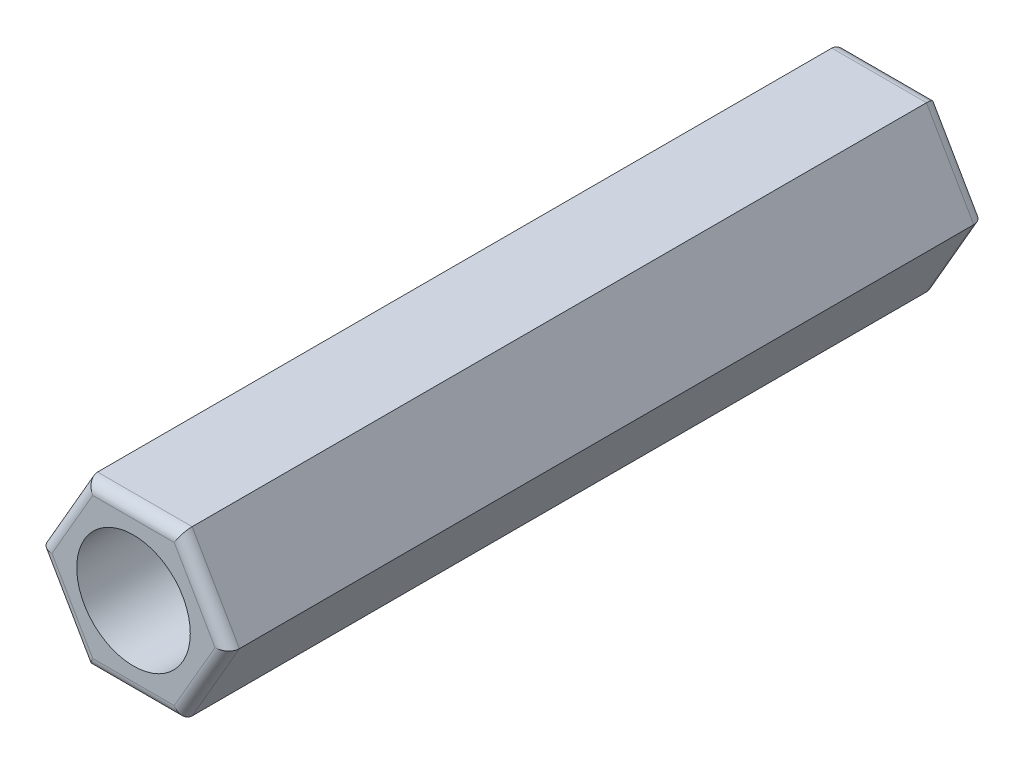
SolidWorks part; units mm, degrees
ref_plane "Front Plane" through (0, 0, 0) normal (0, 0, 1) x (1, 0, 0)
ref_plane "Top Plane" through (0, 0, 0) normal (0, 1, 0) x (1, 0, 0)
ref_plane "Right Plane" through (0, 0, 0) normal (1, 0, 0) x (0, 0, -1)
sketch "Sketch1" plane through (0, 0, 0) normal (0, 0, 1) x (1, 0, 0)
  line L1 (2.5, 0) -> (1.25, 2.1651)
  line L2 (1.25, 2.1651) -> (-1.25, 2.1651)
  line L3 (-1.25, 2.1651) -> (-2.5, 0)
  line L4 (-2.5, 0) -> (-1.25, -2.1651)
  line L5 (-1.25, -2.1651) -> (1.25, -2.1651)
  line L6 (1.25, -2.1651) -> (2.5, 0)
  circle A0 centre (0, 0) radius 2.1651 construction
  circle A1 centre (0, 0) radius 1.5
  dimension "D2" = 3
  dimension "D1" = 5
extrude "Boss-Extrude1" add sketch "Sketch1" along normal blind 20
fillet "Fillet5" radius 0.3 6 edges at (1.875, -1.0825, 20) (1.875, 1.0825, 20) (0, 2.1651, 20) (-1.875, 1.0825, 20) (-1.875, -1.0825, 20) (0, -2.1651, 20)
fillet "Fillet6" radius 0.3 6 edges at (0, -2.1651, 0) (-1.875, -1.0825, 0) (-1.875, 1.0825, 0) (1.875, 1.0825, 0) (0, 2.1651, 0) (1.875, -1.0825, 0)
